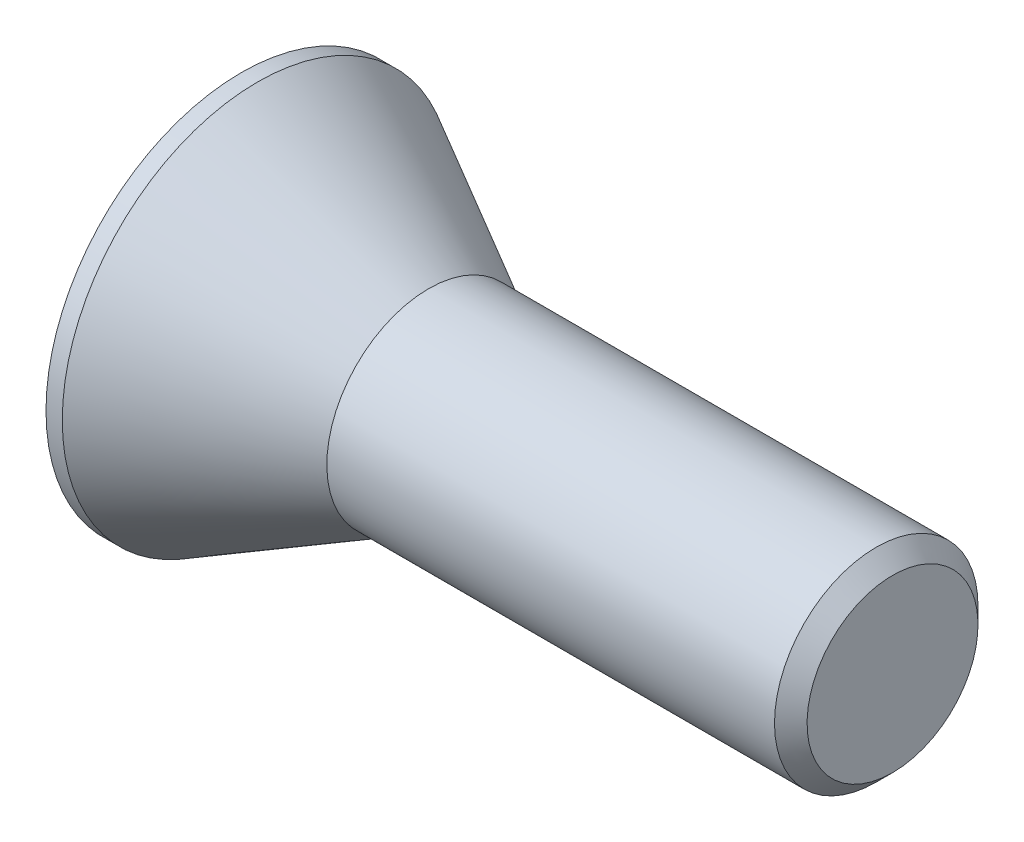
SolidWorks part; units mm, degrees
material "铸造碳钢"
ref_plane "前视基准面" through (0, 0, 0) normal (0, 0, 1) x (1, 0, 0)
ref_plane "上视基准面" through (0, 0, 0) normal (0, 1, 0) x (1, 0, 0)
ref_plane "右视基准面" through (0, 0, 0) normal (1, 0, 0) x (0, 0, -1)
other "Configuration Table"
sketch "草图1" plane through (0, 0, 0) normal (0, 0, 1) x (1, 0, 0)
  line L0 (0, 0) -> (0, -2.4)
  line L1 (0, -2.4) -> (0.2, -2.4)
  line L2 (0.2, -2.4) -> (2.3, -1.25)
  line L3 (2.3, -1.25) -> (8, -1.25)
  line L4 (8, -1.25) -> (8, 0)
  line L5 (8, 0) -> (0, 0)
  dimension "D1" = 1.25
  dimension "D2" = 2.4
  dimension "D3" = 2.3
  dimension "D4" = 8
  dimension "D5" = 0.2
revolve "旋转1" add sketch "草图1" angle 360 about L5
sketch "草图2" plane through (0, 0, 0) normal (-1, 0, 0) x (0, 0, 1)
  line L0 (0, 0) -> (2.4, 0) construction
  line L1 (0.866, 0) -> (0.433, 0.75)
  line L2 (0.433, 0.75) -> (-0.433, 0.75)
  line L3 (-0.433, 0.75) -> (-0.866, 0)
  line L4 (-0.866, 0) -> (-0.433, -0.75)
  line L5 (-0.433, -0.75) -> (0.433, -0.75)
  line L6 (0.433, -0.75) -> (0.866, 0)
  circle A0 centre (0, 0) radius 0.75 construction
  circle A1 centre (0, 0) radius 2.4 construction
  dimension "D1" = 1.5
  dimension "D2" = 60
extrude "切除-拉伸1" cut sketch "草图2" against normal blind 0.4
chamfer "倒角1" distance 0.2 angle 45 1 edges at (8, 1.25, 0)
